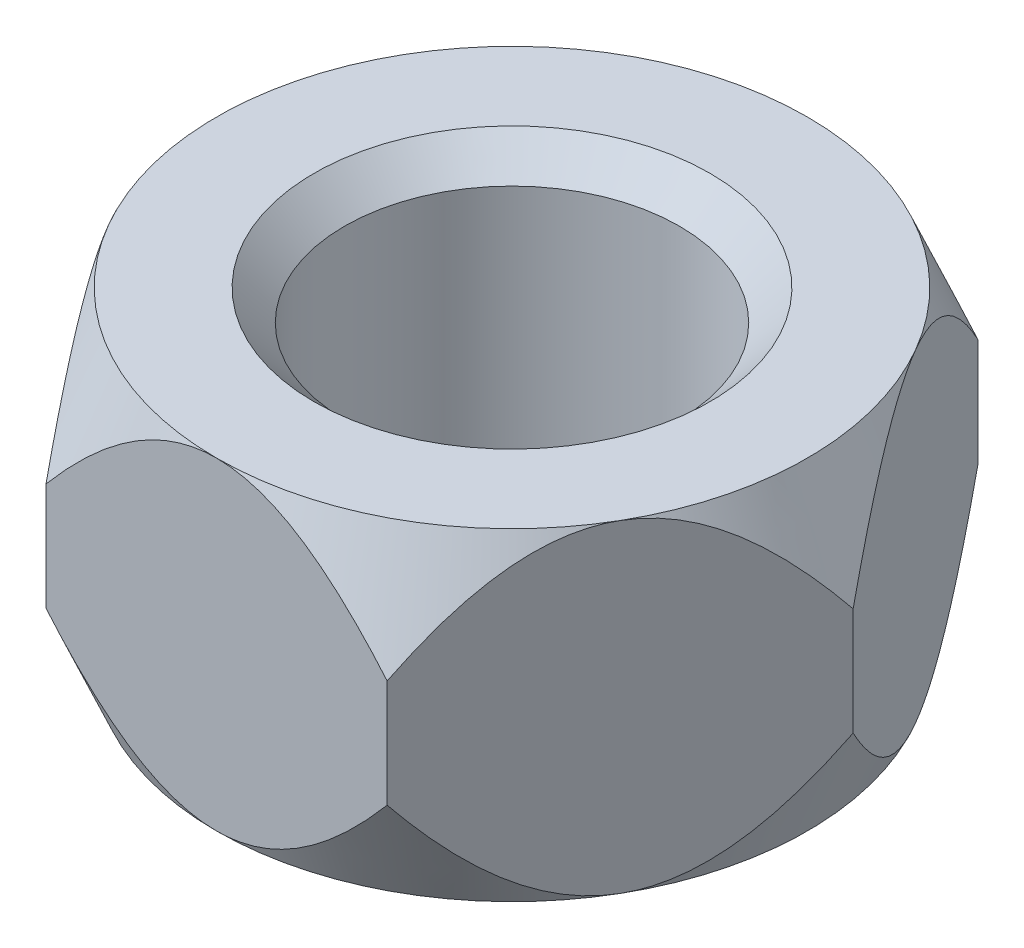
SolidWorks part; units mm, degrees
ref_plane "前视基准面" through (0, 0, 0) normal (0, 0, 1) x (1, 0, 0)
ref_plane "上视基准面" through (0, 0, 0) normal (0, 1, 0) x (1, 0, 0)
ref_plane "右视基准面" through (0, 0, 0) normal (1, 0, 0) x (0, 0, -1)
sketch "草图1" plane through (0, 0, 0) normal (0, 1, 0) x (1, 0, 0)
  line L1 (4.3301, 7.5) -> (-4.3301, 7.5)
  line L2 (-4.3301, 7.5) -> (-8.6603, 0)
  line L3 (-8.6603, 0) -> (-4.3301, -7.5)
  line L4 (-4.3301, -7.5) -> (4.3301, -7.5)
  line L5 (4.3301, -7.5) -> (8.6603, 0)
  line L6 (8.6603, 0) -> (4.3301, 7.5)
  circle A0 centre (0, 0) radius 7.5 construction
  dimension "D1" = 15
extrude "凸台-拉伸1" add sketch "草图1" along normal blind 8.2
sketch "草图2" plane through (0, 8.2, 0) normal (0, 1, 0) x (1, 0, 0)
  line L0 (8.6603, 0) -> (4.3301, 7.5) construction
  circle A0 centre (0, 0) radius 7.5
extrude "切除-拉伸1" cut sketch "草图2" against normal blind 8.2 draft 23 flip side to cut
sketch "草图3" plane through (0, 0, 0) normal (0, -1, 0) x (1, 0, 0)
  line L0 (4.3301, 7.5) -> (8.6603, 0) construction
  circle A0 centre (0, 0) radius 7.5
extrude "切除-拉伸2" cut sketch "草图3" against normal blind 8.2 draft 23 flip side to cut
hole_wizard "M10 螺纹孔1" positions "草图4" profile "草图5" tap size "M10" standard "GB" end condition through all
sketch "草图4" plane through (0, 8.2, 0) normal (0, 1, 0) x (1, 0, 0)
  point P0 (0, 0)
sketch "草图5" plane through (0, 8.2, 0) normal (1, 0, 0) x (0, 0, 1)
  line L0 (0, 0) -> (0, 8.2)
  line L1 (0, 8.2) -> (4.25, 8.2)
  line L2 (4.25, 8.2) -> (4.25, 0.775)
  line L3 (4.25, 0.775) -> (5.025, 0)
  line L5 (5.025, 0) -> (0, 0)
  line L6 (-4.25, 0.775) -> (-5.025, 0) construction
  line L11 (0, -6.35) -> (0, 107.95) construction
  dimension "通孔螺纹孔钻头直径" = 8.5
  dimension "通孔螺纹孔钻头深度" = 8.2
  dimension "近端锥形沉头孔直径" = 10.05
  dimension "近端锥形沉头孔角度" = 90
cosmetic thread "孔螺蚊线1" parameters "D2"=10
